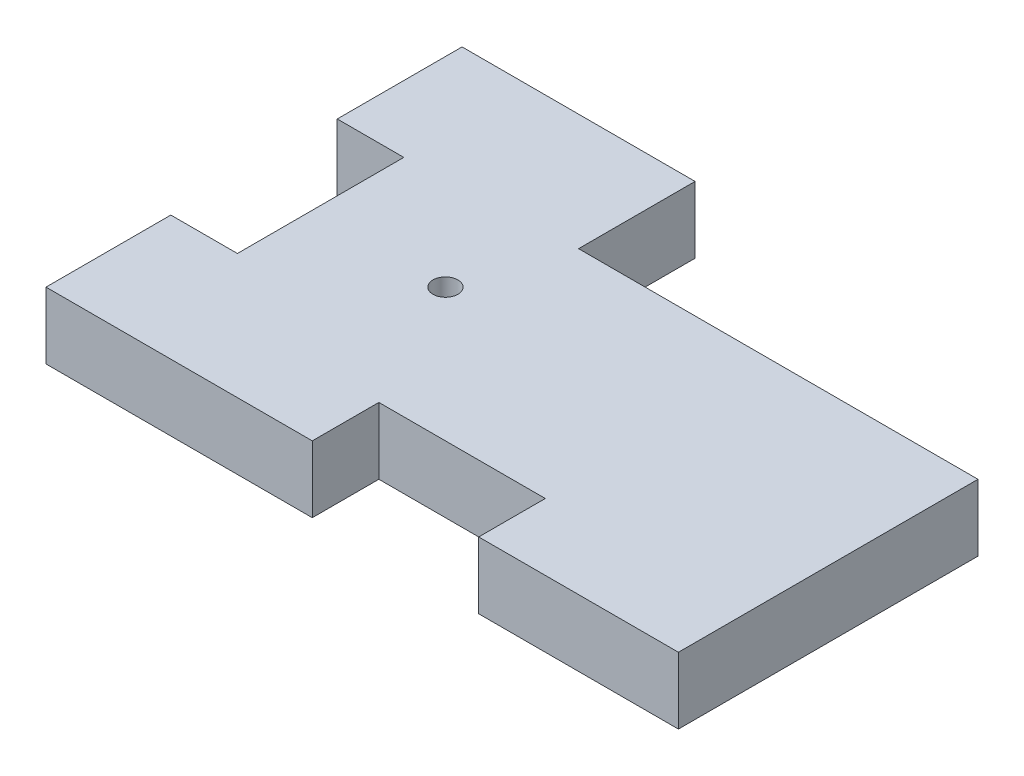
SolidWorks part; units mm, degrees
material "Maple"
ref_plane "Front Plane" through (0, 0, 0) normal (0, 0, 1) x (1, 0, 0)
ref_plane "Top Plane" through (0, 0, 0) normal (0, 1, 0) x (1, 0, 0)
ref_plane "Right Plane" through (0, 0, 0) normal (1, 0, 0) x (0, 0, -1)
sketch "Sketch1" plane through (0, 0, 0) normal (0, 1, 0) x (1, 0, 0)
  line L1 (0, 0) -> (38, 0)
  line L2 (0, 0) -> (0, -25)
  line L3 (0, -25) -> (38, -25)
  line L4 (38, 0) -> (38, -25)
  dimension "D1" = 38
  dimension "D2" = 25
extrude "Boss-Extrude1" add sketch "Sketch1" along normal blind 4
sketch "Sketch2" plane through (0, 4, 0) normal (0, 1, 0) x (1, 0, 0)
  line L0 (38, 0) -> (0, 0) construction
  line L1 (38, 0) -> (14, 0)
  line L2 (38, 0) -> (38, -7)
  line L3 (38, -7) -> (14, -7)
  line L4 (14, 0) -> (14, -7)
  line L5 (38, -25) -> (38, 0) construction
  dimension "D1" = 7
  dimension "D2" = 24
extrude "Cut-Extrude1" cut sketch "Sketch2" against normal through all
sketch "Sketch3" plane through (0, 0, 0) normal (0, -1, 0) x (1, 0, 0)
  line L0 (0, 0) -> (0, 25) construction
  line L1 (4, 7.5) -> (0, 7.5)
  line L2 (4, 7.5) -> (4, 17.5)
  line L3 (4, 17.5) -> (0, 17.5)
  line L4 (0, 7.5) -> (0, 17.5)
extrude "Cut-Extrude2" cut sketch "Sketch3" against normal through all
sketch "Sketch4" plane through (0, 0, 0) normal (0, -1, 0) x (-1, 0, 0)
  line L0 (0, -25) -> (-38, -25) construction
  line L1 (-16, -21) -> (-26, -21)
  line L2 (-16, -21) -> (-16, -25)
  line L3 (-16, -25) -> (-26, -25)
  line L4 (-26, -21) -> (-26, -25)
extrude "Cut-Extrude3" cut sketch "Sketch4" against normal through all
sketch "Sketch5" plane through (0, 4, 0) normal (0, 1, 0) x (1, 0, 0)
  circle A0 centre (12, -13) radius 0.75
  dimension "D1" = 1.5
extrude "Cut-Extrude4" cut sketch "Sketch5" against normal through all
